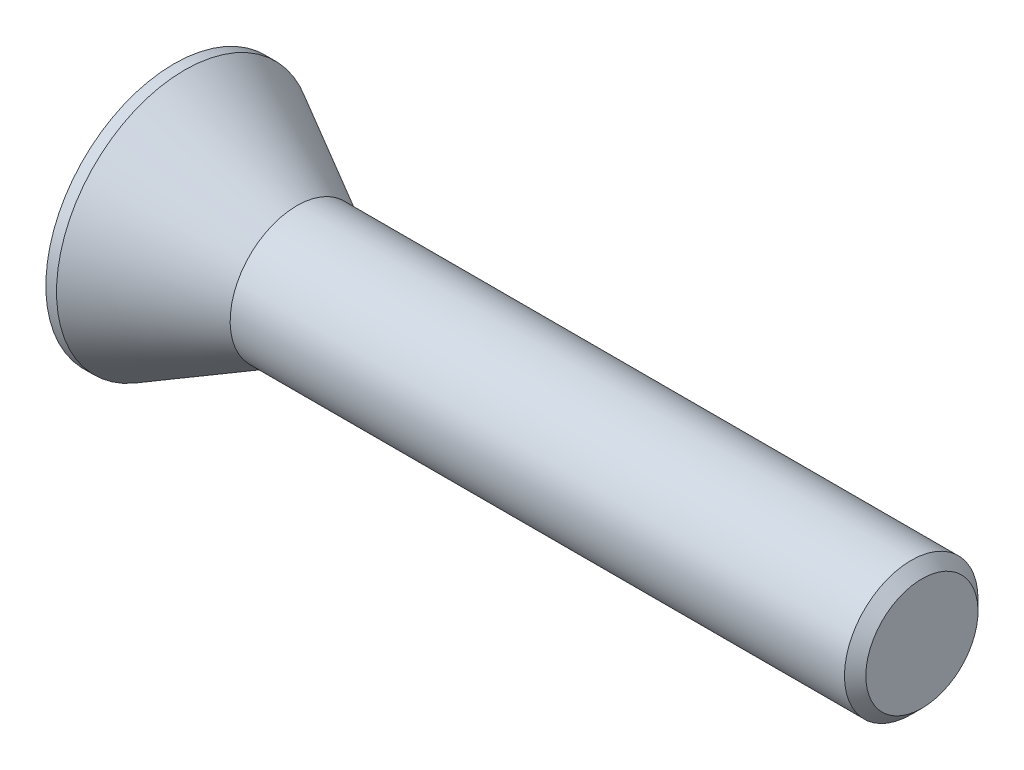
SolidWorks part; units mm, degrees
material "铸造碳钢"
ref_plane "前视基准面" through (0, 0, 0) normal (0, 0, 1) x (1, 0, 0)
ref_plane "上视基准面" through (0, 0, 0) normal (0, 1, 0) x (1, 0, 0)
ref_plane "右视基准面" through (0, 0, 0) normal (1, 0, 0) x (0, 0, -1)
other "Configuration Table"
sketch "草图1" plane through (0, 0, 0) normal (0, 0, 1) x (1, 0, 0)
  line L0 (0, 0) -> (0, -2.4)
  line L1 (0, -2.4) -> (0.2, -2.4)
  line L2 (0.2, -2.4) -> (2.3, -1.25)
  line L3 (2.3, -1.25) -> (14, -1.25)
  line L4 (14, -1.25) -> (14, 0)
  line L5 (14, 0) -> (0, 0)
  dimension "D1" = 1.25
  dimension "D2" = 2.4
  dimension "D3" = 2.3
  dimension "D4" = 14
  dimension "D5" = 0.2
revolve "旋转1" add sketch "草图1" angle 360 about L5
sketch "草图2" plane through (0, 0, 0) normal (-1, 0, 0) x (0, 0, 1)
  line L0 (0, 0) -> (2.4, 0) construction
  line L1 (0.866, 0) -> (0.433, 0.75)
  line L2 (0.433, 0.75) -> (-0.433, 0.75)
  line L3 (-0.433, 0.75) -> (-0.866, 0)
  line L4 (-0.866, 0) -> (-0.433, -0.75)
  line L5 (-0.433, -0.75) -> (0.433, -0.75)
  line L6 (0.433, -0.75) -> (0.866, 0)
  circle A0 centre (0, 0) radius 0.75 construction
  circle A1 centre (0, 0) radius 2.4 construction
  dimension "D1" = 1.5
  dimension "D2" = 60
extrude "切除-拉伸1" cut sketch "草图2" against normal blind 0.4
chamfer "倒角1" distance 0.2 angle 45 1 edges at (14, 1.25, 0)
